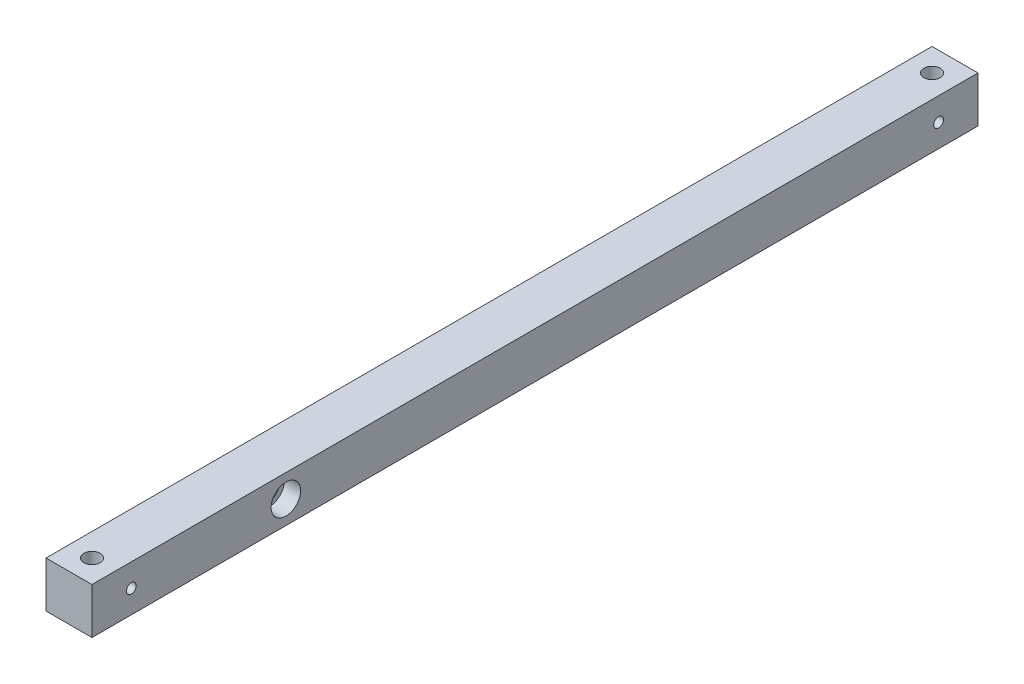
SolidWorks part; units mm, degrees
ref_plane "Ön Düzlem" through (0, 0, 0) normal (0, 0, 1) x (1, 0, 0)
ref_plane "Üst Düzlem" through (0, 0, 0) normal (0, 1, 0) x (1, 0, 0)
ref_plane "Sağ Düzlem" through (0, 0, 0) normal (1, 0, 0) x (0, 0, -1)
sketch "Çizim1" plane through (0, 0, 0) normal (0, 0, 1) x (1, 0, 0)
  line L1 (-14, -14) -> (14, -14)
  line L2 (-14, -14) -> (-14, 14)
  line L3 (-14, 14) -> (14, 14)
  line L4 (14, -14) -> (14, 14)
  line L5 (-14, -14) -> (14, 14) construction
  line L6 (-14, 14) -> (14, -14) construction
  point P0 (0, 0)
  dimension "D1" = 28
  dimension "D2" = 28
extrude "Yükseklik-Ekstrüzyon1" add sketch "Çizim1" along normal mid plane 540
sketch "Çizim3" plane through (0, 14, 0) normal (0, 1, 0) x (1, 0, 0)
  line L0 (-14, -270) -> (-14, 270) construction
  line L1 (-14, -606.7866) -> (14, -606.7866) construction
  line L2 (14, -270) -> (14, 270) construction
  line L3 (14, -270) -> (-14, -270) construction
  line L4 (14, 270) -> (-14, 270) construction
  circle A0 centre (0, 256) radius 5
  circle A1 centre (0, -256) radius 5
  point P11 (0, -606.7866)
  dimension "D1" = 10
  dimension "D2" = 14
  dimension "D3" = 14
extrude "Kes-Ekstrüzyon2" cut sketch "Çizim3" against normal blind 7
sketch "Çizim4" plane through (0, 14, 0) normal (0, 1, 0) x (1, 0, 0)
  circle A0 centre (0, -256) radius 3
  circle A1 centre (0, 256) radius 3
  dimension "D1" = 6
  dimension "D2" = 6
extrude "Kes-Ekstrüzyon3" cut sketch "Çizim4" against normal through all
sketch "Çizim5" plane through (14, 0, 0) normal (1, 0, 0) x (0, 0, -1)
  line L0 (-557.5222, 14) -> (-557.5222, -14) construction
  line L1 (-270, 14) -> (270, 14) construction
  line L2 (-270, -14) -> (270, -14) construction
  circle A0 centre (-151.8, 0) radius 6
  point P8 (-557.5222, 0)
  dimension "D1" = 12
  dimension "D2" = 151.8
extrude "Kes-Ekstrüzyon4" cut sketch "Çizim5" against normal through all
sketch "Çizim6" plane through (14, 0, 0) normal (1, 0, 0) x (0, 0, -1)
  circle A0 centre (-151.8, 0) radius 9
  dimension "D1" = 18
extrude "Kes-Ekstrüzyon5" cut sketch "Çizim6" against normal blind 10
sketch "Çizim7" plane through (14, 0, 0) normal (1, 0, 0) x (0, 0, -1)
  line L0 (270, -14) -> (270, 14) construction
  line L1 (-270, -14) -> (-270, 14) construction
  circle A0 centre (246, 0) radius 3
  circle A1 centre (-246, 0) radius 3
  dimension "D1" = 24
  dimension "D3" = 6
  dimension "D2" = 24
extrude "Kes-Ekstrüzyon6" cut sketch "Çizim7" against normal up to next
sketch "Çizim9" plane through (-14, 0, 0) normal (-1, 0, 0) x (0, 0, 1)
  circle A8 centre (246, 0) radius 5
  circle A9 centre (-246, 0) radius 5
  dimension "D1" = 10
extrude "Kes-Ekstrüzyon8" cut sketch "Çizim9" against normal blind 7
sketch "Sketch2" plane through (0, -14, 0) normal (0, -1, 0) x (1, 0, 0)
  line L0 (-14, 270) -> (14, 270) construction
  circle A0 centre (0, 193.8) radius 3
  circle A1 centre (0, 106.8) radius 3
  dimension "D3" = 6
  dimension "D1" = 76.2
  dimension "D2" = 87
extrude "Cut-Extrude1" cut sketch "Sketch2" against normal blind 16
sketch "Sketch3" plane through (-14, 0, 0) normal (-1, 0, 0) x (0, 0, 1)
  line L0 (270, 14) -> (270, -14) construction
  line L1 (270, 14) -> (-270, 14) construction
  circle A0 centre (116.8, 0) radius 6
  dimension "D1" = 153.2
  dimension "D2" = 12
  dimension "D3" = 14
extrude "Cut-Extrude2" cut sketch "Sketch3" against normal blind 20
sketch "Sketch4" plane through (0, -14, 0) normal (0, -1, 0) x (1, 0, 0)
  line L0 (-14, 270) -> (14, 270) construction
  line L1 (14, 270) -> (14, -270) construction
  circle A0 centre (-2, 116.8) radius 2.5
  dimension "D2" = 5
  dimension "D1" = 153.2
  dimension "D3" = 16
extrude "Cut-Extrude3" cut sketch "Sketch4" against normal blind 10
